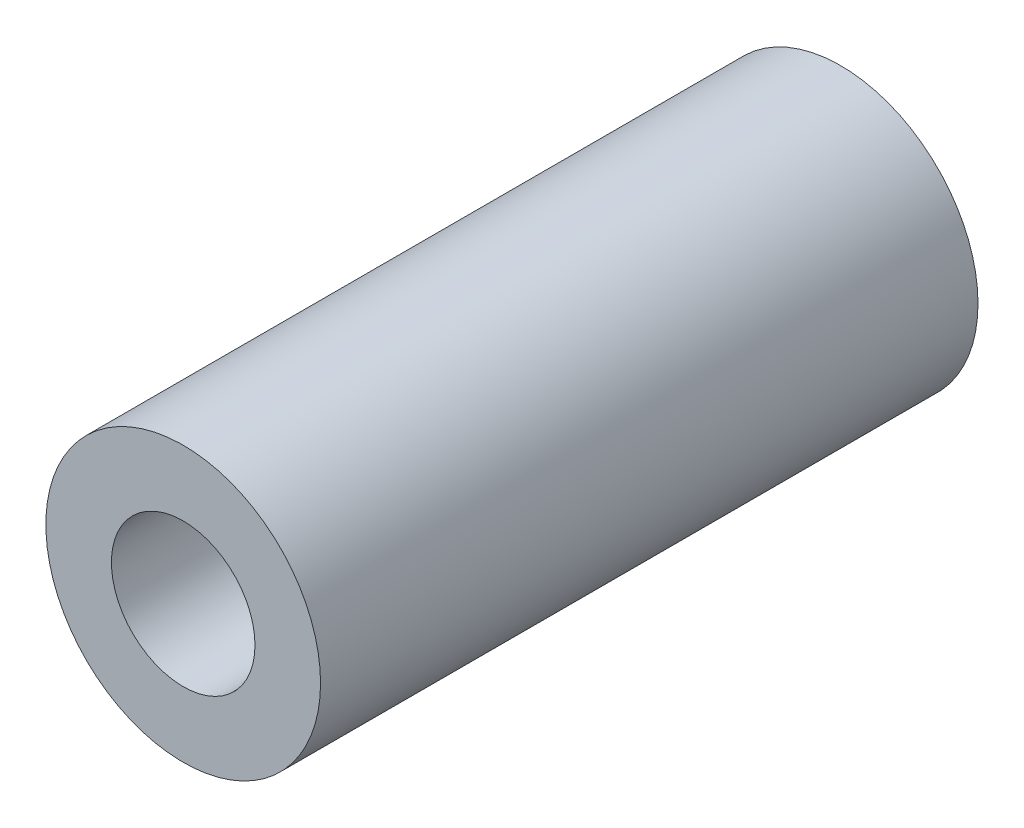
SolidWorks part; units mm, degrees
ref_plane "Front Plane" through (0, 0, 0) normal (0, 0, 1) x (1, 0, 0)
ref_plane "Top Plane" through (0, 0, 0) normal (0, 1, 0) x (1, 0, 0)
ref_plane "Right Plane" through (0, 0, 0) normal (1, 0, 0) x (0, 0, -1)
sketch "Sketch1" plane through (0, 0, 0) normal (0, 0, 1) x (1, 0, 0)
  circle A0 centre (0, 0) radius 4.7625
  circle A1 centre (0, 0) radius 2.4892
  dimension "D1" = 4.9784
  dimension "D2" = 9.525
extrude "Boss-Extrude1" add sketch "Sketch1" along normal mid plane 22.7965 contours A1 | A0
